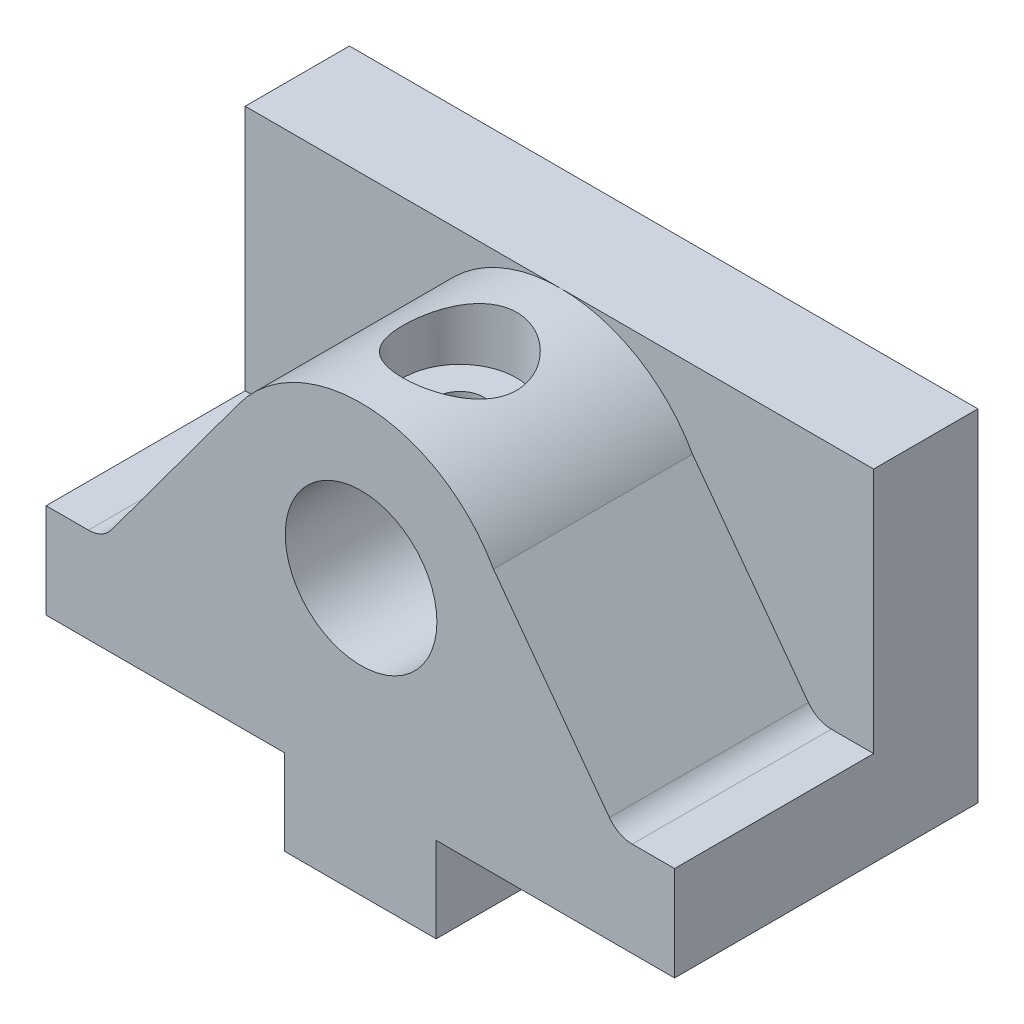
SolidWorks part; units mm, degrees
ref_plane "Front Plane" through (0, 0, 0) normal (0, 0, 1) x (1, 0, 0)
ref_plane "Top Plane" through (0, 0, 0) normal (0, 1, 0) x (1, 0, 0)
ref_plane "Right Plane" through (0, 0, 0) normal (1, 0, 0) x (0, 0, -1)
sketch "Sketch1" plane through (0, 0, 0) normal (0, 0, 1) x (1, 0, 0)
  line L0 (-8, -16) -> (-8, -25)
  line L1 (-33.15, -16) -> (-8, -16)
  line L2 (-33.15, -16) -> (-33.15, -6)
  line L4 (33.15, -16) -> (33.15, -6)
  line L5 (-33.15, -6) -> (-28.6876, -6)
  line L6 (-12.7994, 13.4947) -> (-26.2729, -4.7803)
  line L7 (-8, -25) -> (8, -25)
  line L8 (8, -25) -> (8, -16)
  line L9 (8, -16) -> (33.15, -16)
  line L11 (33.15, -6) -> (28.6876, -6)
  line L12 (12.7994, 13.4947) -> (26.2729, -4.7803)
  arc A0 (14.0487, 11.8002) -> (-12.7994, 13.4947) centre (0.0789, 4) ccw
  arc A1 (-26.2729, -4.7803) -> (-28.6876, -6) centre (-28.6876, -3) cw
  arc A3 (26.2729, -4.7803) -> (28.6876, -6) centre (28.6876, -3) ccw
  circle A5 centre (0.0789, 4) radius 8
  point P0 (0, 0)
  point P1 (0, 0)
  dimension "D6" = 32
  dimension "D10" = 3
  dimension "D2" = 66.3
  dimension "D4" = 16
  dimension "D5" = 9
  dimension "D8" = 10
  dimension "D9" = 53.6
extrude "Boss-Extrude1" add sketch "Sketch1" along normal blind 21
sketch "Sketch2" plane through (0, 0, 0) normal (0, 0, -1) x (-1, 0, 0)
  line L1 (-33.15, -16) -> (33.15, -16)
  line L2 (-33.15, -16) -> (-33.15, 20)
  line L3 (-33.15, 20) -> (33.15, 20)
  line L4 (33.15, -16) -> (33.15, 20)
  dimension "D1" = 66.3
  dimension "D2" = 36
extrude "Boss-Extrude2" add sketch "Sketch2" along normal blind 11
sketch "Sketch19" plane through (0, 20, 0) normal (0, 1, 0) x (1, 0, 0)
  line L0 (0.0789, 0) -> (14.0487, 0) construction
  circle A0 centre (0, -10.5) radius 6
  dimension "D1" = 12
  dimension "D2" = 10.5
extrude "Cut-Extrude7" cut sketch "Sketch19" against normal blind 6
hole_wizard "M6 Tapped Hole1" positions "3DSketch5" profile "Sketch20" tap size "M6" standard "ISO"
sketch3d "3DSketch5"
  line L0 (0, 14, 10.5) -> (0, 19.9998, 10.5) construction
  point P0 (0, 14, 10.5)
sketch "Sketch20" plane through (0, 14, 10.5) normal (1, 0, 0) x (0, 0, 1)
  line L0 (0, 0) -> (0, 2.0004)
  line L1 (0, 2.0004) -> (2.5, 2.0004)
  line L2 (2.5, 2.0004) -> (2.5, 0)
  line L5 (2.5, 0) -> (0, 0)
  line L11 (0, -6.35) -> (0, 107.95) construction
  dimension "Thru Tap Drill Dia." = 5
  dimension "Thru Tap Drill Depth" = 2.0004
cosmetic thread "Hole Thread5" parameters "D2"=6
